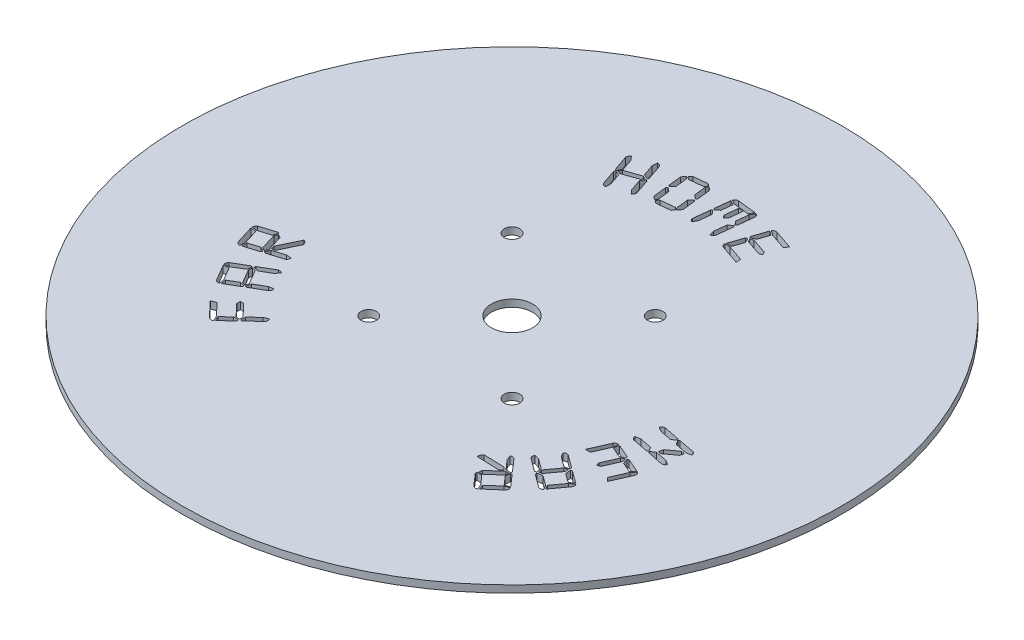
SolidWorks part; units mm, degrees
ref_plane "Front Plane" through (0, 0, 0) normal (0, 0, 1) x (1, 0, 0)
ref_plane "Top Plane" through (0, 0, 0) normal (0, 1, 0) x (1, 0, 0)
ref_plane "Right Plane" through (0, 0, 0) normal (1, 0, 0) x (0, 0, -1)
sketch "Sketch1" plane through (0, 0, 0) normal (0, 1, 0) x (1, 0, 0)
  circle A0 centre (0, 0) radius 146.05
  dimension "D1" = 292.1
extrude "Boss-Extrude1" add sketch "Sketch1" along normal blind 3.175 contours A0
sketch "Sketch2" plane through (0, 3.175, 0) normal (0, 1, 0) x (1, 0, 0)
  line L0 (0, 0) -> (-140.0663, 80.8673) construction
  line L1 (0, 0) -> (140.7974, 81.2894) construction
  line L2 (0, 0) -> (-140.7319, 0) construction
  line L3 (0, 0) -> (0, -157.2555) construction
  arc A0 (65.9911, 38.1) -> (-65.9911, 38.1) centre (0, 0) ccw construction
  arc A1 (65.9911, 38.1) -> (0, -76.2) centre (0, 0) cw construction
  arc A2 (0, -76.2) -> (-65.9911, 38.1) centre (0, 0) cw construction
  circle A3 centre (0, 0) radius 9.144
  text T0 "HOME" font "Digital-7 Mono" height in points 72
  text T1 "NEAR" font "Digital-7 Mono" height in points 72
  text T2 "FAR" font "Digital-7" height in points 72
  dimension "D1" = 120
  dimension "D3" = 76.2
  dimension "D4" = 18.288
  dimension "D2" = 30
extrude "Cut-Extrude1" cut sketch "Sketch2" against normal blind 3.175
sketch "Sketch3" plane through (0, 0, 0) normal (0, -1, 0) x (1, 0, 0)
  line L1 (-31.75, 31.75) -> (31.75, 31.75) construction
  line L2 (-31.75, 31.75) -> (-31.75, -31.75) construction
  line L3 (-31.75, -31.75) -> (31.75, -31.75) construction
  line L4 (31.75, 31.75) -> (31.75, -31.75) construction
  circle A0 centre (-31.75, 31.75) radius 3.429
  circle A1 centre (31.75, 31.75) radius 3.429
  circle A2 centre (31.75, -31.75) radius 3.429
  circle A3 centre (-31.75, -31.75) radius 3.429
  point P4 (31.75, 0)
  point P6 (0, 31.75)
  dimension "D2" = 6.858
  dimension "D3" = 6.858
  dimension "D4" = 6.858
  dimension "D5" = 6.858
  dimension "D1" = 63.5
extrude "Cut-Extrude2" cut sketch "Sketch3" against normal blind 3.175
equation "\"D3@Sketch3\"=\"D2@Sketch3\""
equation "\"D4@Sketch3\"=\"D2@Sketch3\""
equation "\"D5@Sketch3\"=\"D2@Sketch3\""
